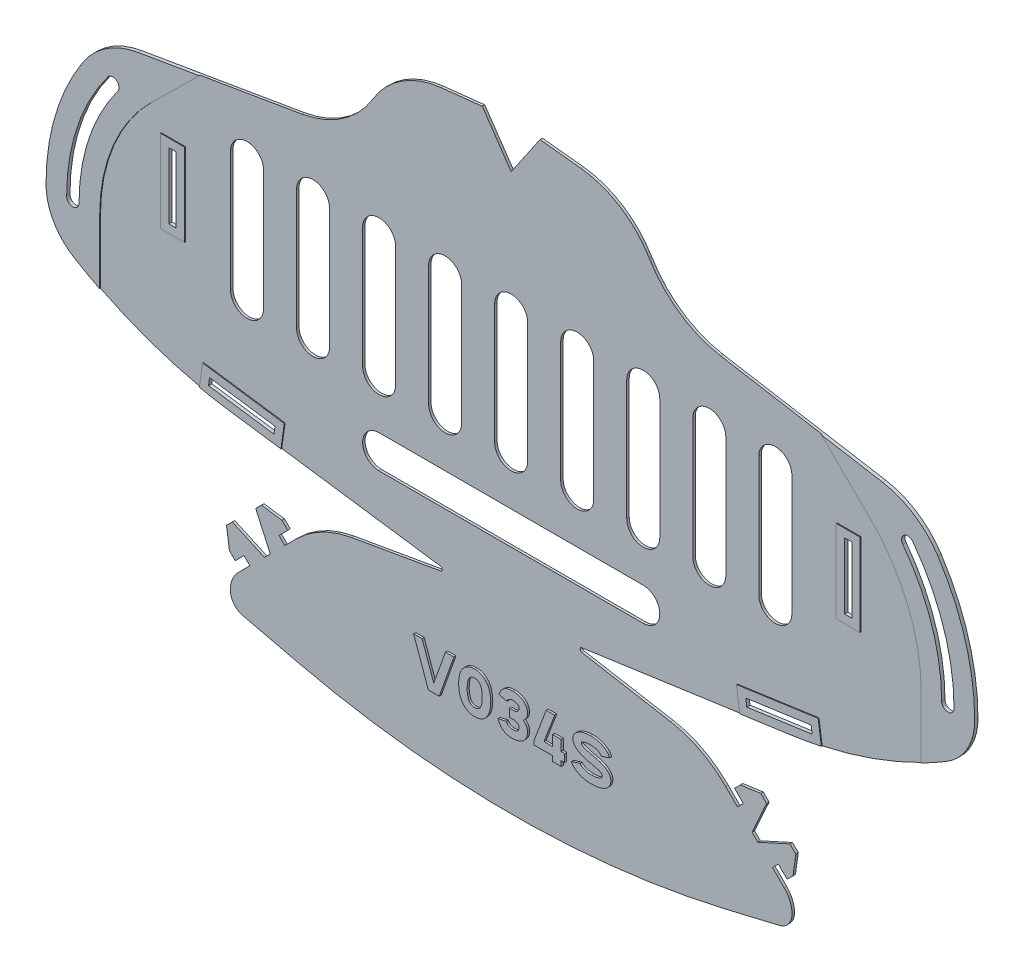
SolidWorks part; units mm, degrees
ref_plane "Front Plane" through (0, 0, 0) normal (0, 0, 1) x (1, 0, 0)
ref_plane "Top Plane" through (0, 0, 0) normal (0, 1, 0) x (1, 0, 0)
ref_plane "Right Plane" through (0, 0, 0) normal (1, 0, 0) x (0, 0, -1)
sketch "Sketch1" plane through (0, 0, 0) normal (0, 0, 1) x (1, 0, 0)
  line L0 (0, 0) -> (0, -145) construction
  line L1 (-14, -102) -> (14, -102) construction
  line L2 (-112.5, -69) -> (112.5, -69) construction
  line L3 (0, -10.2352) -> (-7, 0)
  line L4 (0, -10.2352) -> (7, 0)
  line L5 (7, 0) -> (16.9419, -1.0768)
  line L6 (-90.1804, -30.1909) -> (-50.7439, -23.5)
  line L7 (90.1804, -30.1909) -> (50.7439, -23.5)
  line L8 (-14, -102) -> (-68.2662, -94.2919)
  line L9 (-7, 0) -> (-16.9419, -1.0768)
  line L10 (14, -102) -> (68.2662, -94.2919)
  line L11 (-103.5977, -39) -> (-103.5977, -69) construction
  line L12 (-14, -102) -> (-38.6266, -106.305)
  line L13 (-52, -113.2546) -> (-54.8283, -116.0832)
  line L14 (52, -113.2546) -> (54.8283, -116.0832)
  line L15 (14, -102) -> (38.6266, -106.305)
  line L16 (-54.8283, -116.0832) -> (-56.2426, -114.669)
  line L17 (-56.2426, -114.669) -> (-54.1214, -112.5476)
  line L18 (-54.1214, -112.5476) -> (-55.5356, -111.1334)
  line L19 (-55.5356, -111.1334) -> (-60.4854, -110.4265)
  line L20 (-60.4854, -110.4265) -> (-68.9703, -118.9122)
  line L21 (-64.7275, -123.1546) -> (-63.3132, -124.5688)
  line L22 (-63.3132, -124.5688) -> (-66.1415, -127.3973)
  line L23 (-64.7275, -123.1546) -> (-66.8487, -125.2761)
  line L24 (-66.8487, -125.2761) -> (-68.263, -123.8619)
  line L25 (-68.9703, -118.9122) -> (-68.263, -123.8619)
  line L26 (68.9703, -118.9122) -> (68.263, -123.8619)
  line L27 (66.8487, -125.2761) -> (68.263, -123.8619)
  line L28 (64.7275, -123.1546) -> (66.8487, -125.2761)
  line L29 (63.3132, -124.5688) -> (66.1415, -127.3973)
  line L30 (64.7275, -123.1546) -> (63.3132, -124.5688)
  line L31 (60.4854, -110.4265) -> (68.9703, -118.9122)
  line L32 (55.5356, -111.1334) -> (60.4854, -110.4265)
  line L33 (54.1214, -112.5476) -> (55.5356, -111.1334)
  line L34 (56.2426, -114.669) -> (54.1214, -112.5476)
  line L35 (54.8283, -116.0832) -> (56.2426, -114.669)
  line L36 (-64.9691, -135.8852) -> (-52.4361, -138.8607)
  line L37 (64.9691, -135.8852) -> (52.4361, -138.8607)
  line L38 (-68.9703, -118.9122) -> (-64.7275, -123.1546) construction
  line L39 (-60.4854, -110.4265) -> (-56.2426, -114.669) construction
  arc A0 (-16.9419, -1.0768) -> (-33.4614, -11.6696) centre (-14.5729, -22.9489) ccw
  arc A1 (-33.4614, -11.6696) -> (-50.7439, -23.5) centre (-54.9257, 1.1478) cw
  arc A2 (-103.5977, -39) -> (-90.1804, -30.1909) centre (-86.8349, -49.9091) cw
  arc A3 (-112.5, -69) -> (-103.5977, -39) centre (-57.5, -69) cw
  arc A4 (112.5, -69) -> (103.5977, -39) centre (57.5, -69) ccw
  arc A5 (103.5977, -39) -> (90.1804, -30.1909) centre (86.8349, -49.9091) ccw
  arc A6 (16.9419, -1.0768) -> (33.4614, -11.6696) centre (14.5729, -22.9489) cw
  arc A7 (33.4614, -11.6696) -> (50.7439, -23.5) centre (54.9257, 1.1478) ccw
  arc A8 (-112.5, -69) -> (-105.7111, -81) centre (-98.5, -69) ccw
  arc A9 (-105.7111, -81) -> (-68.2662, -94.2919) centre (-54.2032, 4.7143) ccw
  arc A10 (112.5, -69) -> (105.7111, -81) centre (98.5, -69) cw
  arc A11 (105.7111, -81) -> (68.2662, -94.2919) centre (54.2032, 4.7143) cw
  arc A12 (-38.6266, -106.305) -> (-52, -113.2546) centre (-34.3216, -130.9315) ccw
  arc A13 (38.6266, -106.305) -> (52, -113.2546) centre (34.3216, -130.9315) cw
  arc A14 (-66.1415, -127.3973) -> (-68.0451, -131.9933) centre (-61.5451, -131.9933) ccw
  arc A15 (-68.0451, -131.9933) -> (-64.9691, -135.8852) centre (-64.0451, -131.9933) ccw
  arc A16 (68.0451, -131.9933) -> (64.9691, -135.8852) centre (64.0451, -131.9933) cw
  arc A17 (66.1415, -127.3973) -> (68.0451, -131.9933) centre (61.5451, -131.9933) cw
  arc A19 (-52.4361, -138.8607) -> (0, -145) centre (0, 82) ccw
  arc A20 (52.4361, -138.8607) -> (0, -145) centre (0, 82) cw
  point P8 (0, -102)
  point P11 (0, -69)
  dimension "D5" = 55
  dimension "D11" = 20
  dimension "D13" = 25
  dimension "D16" = 14
  dimension "D15" = 22
  dimension "D18" = 100
  dimension "D22" = 25
  dimension "D31" = 6.5
  dimension "D32" = 4
  dimension "D34" = 227
  dimension "D1" = 145
  dimension "D2" = 28
  dimension "D3" = 43
  dimension "D4" = 76
  dimension "D6" = 225
  dimension "D7" = 14
  dimension "D8" = 12.4
  dimension "D9" = 10
  dimension "D10" = 30
  dimension "D12" = 40
  dimension "D14" = 45.5
  dimension "D17" = 12
  dimension "D19" = 18
  dimension "D20" = 25
  dimension "D21" = 4
  dimension "D23" = 38
  dimension "D24" = 2
  dimension "D25" = 3
  dimension "D26" = 2
  dimension "D27" = 18
  dimension "D29" = 8
  dimension "D30" = 4
extrude "Main Shape" add sketch "Sketch1" along normal blind 0.6
sketch "Sketch2" plane through (0, 0, 0.6) normal (0, 0, 1) x (1, 0, 0)
  line L0 (0, -55) -> (0, 55) construction
  arc A0 (-96.3, -39.9) -> (-106, -69) centre (-57.5, -69) ccw construction
  arc A1 (-97.5, -39) -> (-107.5, -69) centre (-57.5, -69) ccw
  arc A2 (-95.1, -40.8) -> (-104.5, -69) centre (-57.5, -69) ccw
  arc A3 (-95.1, -40.8) -> (-97.5, -39) centre (-96.3, -39.9) ccw
  arc A4 (-107.5, -69) -> (-104.5, -69) centre (-106, -69) ccw
  arc A6 (-103.5977, -39) -> (-112.5, -69) centre (-57.5, -69) ccw construction
  arc A7 (96.3, -39.9) -> (106, -69) centre (57.5, -69) cw construction
  arc A8 (97.5, -39) -> (107.5, -69) centre (57.5, -69) cw
  arc A9 (95.1, -40.8) -> (104.5, -69) centre (57.5, -69) cw
  arc A10 (95.1, -40.8) -> (97.5, -39) centre (96.3, -39.9) cw
  arc A11 (107.5, -69) -> (104.5, -69) centre (106, -69) cw
  point P3 (-103.5111, -53.663)
  point P19 (103.5111, -53.663)
  dimension "D1" = 5
  dimension "D2" = 1.5
extrude "Elastic Attachment Points" cut sketch "Sketch2" against normal through all
sketch "Sketch7" plane through (0, 0, 0.6) normal (0, 0, 1) x (1, 0, 0)
  line L0 (-99.5, -69) -> (-99.5, -84.4384)
  line L1 (-86.8939, -39) -> (-75.3319, -27.6717)
  line L2 (-50.7439, -23.5) -> (-90.1804, -30.1909) construction
  line L3 (-75.3319, -27.6717) -> (-90.1804, -30.1909)
  line L4 (0, -55) -> (0, 55) construction
  line L5 (75.3319, -27.6717) -> (90.1804, -30.1909)
  line L6 (86.8939, -39) -> (75.3319, -27.6717)
  line L7 (99.5, -69) -> (99.5, -84.4384)
  arc A0 (-99.5, -69) -> (-86.8939, -39) centre (-57.5, -69) cw
  arc A1 (-95.1, -40.8) -> (-104.5, -69) centre (-57.5, -69) ccw construction
  arc A2 (-105.7111, -81) -> (-68.2662, -94.2919) centre (-54.2032, 4.7143) ccw construction
  arc A3 (-112.5, -69) -> (-105.7111, -81) centre (-98.5, -69) ccw construction
  arc A4 (-103.5977, -39) -> (-112.5, -69) centre (-57.5, -69) ccw construction
  arc A5 (-90.1804, -30.1909) -> (-103.5977, -39) centre (-86.8349, -49.9091) ccw construction
  arc A6 (-105.7111, -81) -> (-99.5, -84.4384) centre (-54.2032, 4.7143) ccw
  arc A7 (-112.5, -69) -> (-105.7111, -81) centre (-98.5, -69) ccw
  arc A8 (-103.5977, -39) -> (-112.5, -69) centre (-57.5, -69) ccw
  arc A9 (-90.1804, -30.1909) -> (-103.5977, -39) centre (-86.8349, -49.9091) ccw
  arc A10 (90.1804, -30.1909) -> (103.5977, -39) centre (86.8349, -49.9091) cw
  arc A11 (103.5977, -39) -> (112.5, -69) centre (57.5, -69) cw
  arc A12 (112.5, -69) -> (105.7111, -81) centre (98.5, -69) cw
  arc A13 (105.7111, -81) -> (99.5, -84.4384) centre (54.2032, 4.7143) cw
  arc A14 (99.5, -69) -> (86.8939, -39) centre (57.5, -69) ccw
  arc A15 (-107.5, -69) -> (-104.5, -69) centre (-106, -69) ccw construction
  arc A16 (-95.1, -40.8) -> (-97.5, -39) centre (-96.3, -39.9) ccw construction
  arc A17 (-97.5, -39) -> (-107.5, -69) centre (-57.5, -69) ccw construction
  arc A18 (-107.5, -69) -> (-104.5, -69) centre (-106, -69) ccw
  arc A19 (-95.1, -40.8) -> (-97.5, -39) centre (-96.3, -39.9) ccw
  arc A20 (-95.1, -40.8) -> (-104.5, -69) centre (-57.5, -69) ccw
  arc A21 (-97.5, -39) -> (-107.5, -69) centre (-57.5, -69) ccw
  arc A22 (104.5, -69) -> (107.5, -69) centre (106, -69) ccw construction
  arc A23 (97.5, -39) -> (95.1, -40.8) centre (96.3, -39.9) ccw construction
  arc A24 (104.5, -69) -> (95.1, -40.8) centre (57.5, -69) ccw construction
  arc A25 (107.5, -69) -> (97.5, -39) centre (57.5, -69) ccw construction
  arc A26 (104.5, -69) -> (107.5, -69) centre (106, -69) ccw
  arc A27 (97.5, -39) -> (95.1, -40.8) centre (96.3, -39.9) ccw
  arc A28 (104.5, -69) -> (95.1, -40.8) centre (57.5, -69) ccw
  arc A29 (107.5, -69) -> (97.5, -39) centre (57.5, -69) ccw
  dimension "D1" = 5
extrude "Reinforced Attachment Points" add sketch "Sketch7" along normal blind 0.2
sketch "Sketch6" plane through (0, 0, 0.6) normal (0, 0, 1) x (1, 0, 0)
  line L0 (-73.1225, -91.5821) -> (-57.2815, -93.8322)
  line L1 (-57.2815, -93.8322) -> (-57.0283, -92.05)
  line L2 (-57.0283, -92.05) -> (-72.8693, -89.8)
  line L3 (-72.8693, -89.8) -> (-73.1225, -91.5821)
  line L4 (-68.2662, -94.2919) -> (-14, -102) construction
  line L5 (-64.9488, -90.925) -> (-65.202, -92.7071) construction
  line L13 (0, -0.44) -> (0, 0.44) construction
  line L14 (64.9488, -90.925) -> (65.202, -92.7071) construction
  line L15 (73.1225, -91.5821) -> (72.8693, -89.8)
  line L16 (57.0283, -92.05) -> (57.2815, -93.8322)
  line L22 (57.0283, -92.05) -> (72.8693, -89.8)
  line L24 (73.1225, -91.5821) -> (57.2815, -93.8322)
  dimension "D1" = 2
  dimension "D2" = 16
  dimension "D3" = 52
  dimension "D4" = 1.8
extrude "Tab Slits" cut sketch "Sketch6" against normal through all
sketch "Sketch9" plane through (0, 0, 0.6) normal (0, 0, 1) x (1, 0, 0)
  line L4 (-57.2815, -93.8322) -> (-57.0283, -92.05) construction
  line L5 (-73.1225, -91.5821) -> (-57.2815, -93.8322) construction
  line L6 (-72.8693, -89.8) -> (-73.1225, -91.5821) construction
  line L7 (-57.0283, -92.05) -> (-72.8693, -89.8) construction
  line L12 (-57.2815, -93.8322) -> (-57.0283, -92.05)
  line L13 (-73.1225, -91.5821) -> (-57.2815, -93.8322)
  line L14 (-72.8693, -89.8) -> (-73.1225, -91.5821)
  line L15 (-57.0283, -92.05) -> (-72.8693, -89.8)
  line L16 (-55.5826, -96.0935) -> (-54.767, -90.3512)
  line L17 (-68.2662, -94.2919) -> (-14, -102) construction
  line L18 (-54.767, -90.3512) -> (-74.5682, -87.5386)
  line L19 (-74.5682, -87.5386) -> (-75.3475, -93.0248)
  line L20 (-68.2662, -94.2919) -> (-55.5826, -96.0935)
  line L21 (0, -0.44) -> (0, 0.44) construction
  line L22 (68.2662, -94.2919) -> (55.5826, -96.0935)
  line L23 (74.5682, -87.5386) -> (75.3475, -93.0248)
  line L24 (54.767, -90.3512) -> (74.5682, -87.5386)
  line L25 (55.5826, -96.0935) -> (54.767, -90.3512)
  line L26 (57.0283, -92.05) -> (72.8693, -89.8)
  line L27 (72.8693, -89.8) -> (73.1225, -91.5821)
  line L28 (73.1225, -91.5821) -> (57.2815, -93.8322)
  line L29 (57.2815, -93.8322) -> (57.0283, -92.05)
  arc A0 (-99.5, -84.4384) -> (-68.2662, -94.2919) centre (-54.2032, 4.7143) ccw construction
  arc A1 (-75.3475, -93.0248) -> (-68.2662, -94.2919) centre (-54.2032, 4.7143) ccw
  arc A2 (75.3475, -93.0248) -> (68.2662, -94.2919) centre (54.2032, 4.7143) cw
  dimension "D1" = 2
  dimension "D2" = 2
  dimension "D3" = 2
extrude "Reinforced Tab Slits" add sketch "Sketch9" along normal blind 0.2
sketch "Sketch11" plane through (0, 0, 0.6) normal (0, 0, 1) x (1, 0, 0)
  line L0 (-67.5562, -117.4979) -> (-59.7778, -121.0331)
  line L1 (-60.4854, -110.4265) -> (-68.9703, -118.9122) construction
  line L2 (-59.7778, -121.0331) -> (-58.3637, -119.6188)
  line L3 (-58.3637, -119.6188) -> (-61.8996, -111.8408)
  line L4 (-61.8996, -111.8408) -> (-67.5562, -117.4979)
  line L6 (-58.3637, -119.6188) -> (-54.8283, -116.0832) construction
  line L7 (-59.7778, -121.0331) -> (-63.3132, -124.5688) construction
  line L10 (0, -0.44) -> (0, 0.44) construction
  line L11 (59.7778, -121.0331) -> (63.3132, -124.5688) construction
  line L12 (58.3637, -119.6188) -> (54.8283, -116.0832) construction
  line L13 (61.8996, -111.8408) -> (67.5562, -117.4979)
  line L14 (58.3637, -119.6188) -> (61.8996, -111.8408)
  line L15 (59.7778, -121.0331) -> (58.3637, -119.6188)
  line L16 (67.5562, -117.4979) -> (59.7778, -121.0331)
  dimension "D1" = 2
  dimension "D2" = 2
  dimension "D3" = 5
extrude "Tab Flex Relief" cut sketch "Sketch11" against normal through all both and the other way through all
sketch "Sketch3" plane through (0, 0, 0.6) normal (0, 0, 1) x (1, 0, 0)
  line L3 (0, -10.2352) -> (0, -145) construction
  line L4 (-106, -69) -> (-96.3, -69) construction
  line L5 (-96.3, -69) -> (-96.3, -39.9) construction
  line L427 (0, -39.9) -> (0, -69) construction
  line L428 (4, -39.9) -> (4, -69)
  line L429 (-4, -39.9) -> (-4, -69)
  line L444 (-16, -39.9) -> (-16, -69) construction
  line L447 (-12, -39.9) -> (-12, -69)
  line L450 (-20, -39.9) -> (-20, -69)
  line L451 (-32, -39.9) -> (-32, -69) construction
  line L455 (-28, -39.9) -> (-28, -69)
  line L456 (-36, -39.9) -> (-36, -69)
  line L836 (-32, -85) -> (32, -85) construction
  line L837 (-32, -81) -> (32, -81)
  line L838 (-32, -89) -> (32, -89)
  line L839 (-64, -73) -> (64, -73) construction
  line L933 (-48, -39.9) -> (-48, -69) construction
  line L934 (-44, -39.9) -> (-44, -69)
  line L935 (-52, -39.9) -> (-52, -69)
  line L936 (-64, -39.9) -> (-64, -69) construction
  line L937 (-60, -39.9) -> (-60, -69)
  line L938 (-68, -39.9) -> (-68, -69)
  line L939 (16, -39.9) -> (16, -69) construction
  line L940 (12, -39.9) -> (12, -69)
  line L941 (20, -39.9) -> (20, -69)
  line L942 (32, -39.9) -> (32, -69) construction
  line L943 (28, -39.9) -> (28, -69)
  line L944 (36, -39.9) -> (36, -69)
  line L945 (48, -39.9) -> (48, -69) construction
  line L946 (44, -39.9) -> (44, -69)
  line L947 (52, -39.9) -> (52, -69)
  line L948 (64, -39.9) -> (64, -69) construction
  line L949 (60, -39.9) -> (60, -69)
  line L950 (68, -39.9) -> (68, -69)
  arc A2 (-52.4361, -138.8607) -> (52.4361, -138.8607) centre (0, 82) ccw construction
  arc A21 (4, -39.9) -> (-4, -39.9) centre (0, -39.9) ccw
  arc A22 (-4, -69) -> (4, -69) centre (0, -69) ccw
  arc A23 (-12, -39.9) -> (-20, -39.9) centre (-16, -39.9) ccw
  arc A24 (-20, -69) -> (-12, -69) centre (-16, -69) ccw
  arc A25 (-28, -39.9) -> (-36, -39.9) centre (-32, -39.9) ccw
  arc A26 (-36, -69) -> (-28, -69) centre (-32, -69) ccw
  arc A27 (-44, -39.9) -> (-52, -39.9) centre (-48, -39.9) ccw
  arc A28 (-52, -69) -> (-44, -69) centre (-48, -69) ccw
  arc A29 (-60, -39.9) -> (-68, -39.9) centre (-64, -39.9) ccw
  arc A30 (-68, -69) -> (-60, -69) centre (-64, -69) ccw
  arc A31 (12, -39.9) -> (20, -39.9) centre (16, -39.9) cw
  arc A32 (20, -69) -> (12, -69) centre (16, -69) cw
  arc A33 (28, -39.9) -> (36, -39.9) centre (32, -39.9) cw
  arc A34 (36, -69) -> (28, -69) centre (32, -69) cw
  arc A35 (44, -39.9) -> (52, -39.9) centre (48, -39.9) cw
  arc A36 (52, -69) -> (44, -69) centre (48, -69) cw
  arc A37 (60, -39.9) -> (68, -39.9) centre (64, -39.9) cw
  arc A38 (68, -69) -> (60, -69) centre (64, -69) cw
  arc A39 (-32, -81) -> (-32, -89) centre (-32, -85) ccw
  arc A40 (32, -89) -> (32, -81) centre (32, -85) ccw
  point P3 (-16, -54.45)
  point P18 (-32, -54.45)
  point P30 (-48, -54.45)
  point P37 (-64, -54.45)
  point P43 (16, -54.45)
  point P50 (32, -54.45)
  point P57 (48, -54.45)
  point P64 (64, -54.45)
  point P71 (0, -85)
  point P414 (0, -54.45)
  dimension "D5" = 8
  dimension "D1" = 8
  dimension "D2" = 5
  dimension "D3" = 8
  dimension "D4" = 8
extrude "Breathing Slits" cut sketch "Sketch3" against normal through all
sketch "Sketch8" plane through (0, 0, 0.6) normal (0, 0, 1) x (1, 0, 0)
  line L0 (-67.0266, -128.5) -> (67.0266, -128.5) construction
  line L1 (0, -10.2352) -> (0, -145) construction
  arc A0 (-52.4361, -138.8607) -> (52.4361, -138.8607) centre (0, 82) ccw construction
  arc A1 (-66.1415, -127.3973) -> (-68.0451, -131.9933) centre (-61.5451, -131.9933) ccw construction
  text T0 "<b>V034S</b>" font "Double Porter 3" height 10
  point P9 (0, -128.5)
  dimension "D2" = 16.5
extrude "Version Number" add sketch "Sketch8" along normal blind 0.5
fillet "Fillet1" radius 0.5 2 edges at (-14, -102, 0.3) (14, -102, 0.3)
sketch "Sketch12" plane through (0, 0, 0.6) normal (0, 0, 1) x (1, 0, 0)
  line L0 (-106, -69) -> (-96.3, -69) construction
  line L1 (-96.3, -69) -> (-96.3, -39.9) construction
  line L2 (-82.7459, -46.45) -> (-80.9459, -46.45)
  line L3 (-82.7459, -46.45) -> (-82.7459, -62.45)
  line L4 (-82.7459, -62.45) -> (-80.9459, -62.45)
  line L5 (-80.9459, -46.45) -> (-80.9459, -62.45)
  line L6 (0, -10.2352) -> (0, -145) construction
  line L9 (80.9459, -46.45) -> (80.9459, -62.45)
  line L10 (82.7459, -62.45) -> (80.9459, -62.45)
  line L11 (82.7459, -46.45) -> (82.7459, -62.45)
  line L12 (82.7459, -46.45) -> (80.9459, -46.45)
  arc A1 (-52.4361, -138.8607) -> (52.4361, -138.8607) centre (0, 82) ccw construction
  point P9 (0, 0)
  point P13 (-96.3, -54.45)
  point P18 (-82.7459, -54.45)
  dimension "D1" = 16
  dimension "D2" = 1.8
  dimension "D3" = 80.9459
extrude "Tab Overlay Slit" cut sketch "Sketch12" against normal through all both and the other way through all
sketch "Sketch13" plane through (0, 0, 0.6) normal (0, 0, 1) x (1, 0, 0)
  line L0 (-80.9459, -62.45) -> (-82.7459, -62.45) construction
  line L1 (-84.7459, -44.45) -> (-78.9459, -44.45)
  line L2 (-84.7459, -44.45) -> (-84.7459, -64.45)
  line L3 (-84.7459, -64.45) -> (-78.9459, -64.45)
  line L4 (-78.9459, -44.45) -> (-78.9459, -64.45)
  line L5 (-82.7459, -62.45) -> (-82.7459, -46.45) construction
  line L6 (-80.9459, -46.45) -> (-80.9459, -62.45) construction
  line L7 (-82.7459, -46.45) -> (-80.9459, -46.45) construction
  line L8 (-80.9459, -62.45) -> (-82.7459, -62.45)
  line L9 (-80.9459, -46.45) -> (-80.9459, -62.45)
  line L10 (-82.7459, -46.45) -> (-80.9459, -46.45)
  line L11 (-82.7459, -62.45) -> (-82.7459, -46.45)
  line L12 (0, -0.44) -> (0, 0.44) construction
  line L13 (82.7459, -62.45) -> (82.7459, -46.45)
  line L14 (82.7459, -46.45) -> (80.9459, -46.45)
  line L15 (80.9459, -46.45) -> (80.9459, -62.45)
  line L16 (80.9459, -62.45) -> (82.7459, -62.45)
  line L17 (78.9459, -44.45) -> (78.9459, -64.45)
  line L18 (84.7459, -64.45) -> (78.9459, -64.45)
  line L19 (84.7459, -44.45) -> (84.7459, -64.45)
  line L20 (84.7459, -44.45) -> (78.9459, -44.45)
  point P8 (-81.8459, -64.45)
  point P9 (-81.8459, -62.45)
  point P10 (-82.7459, -54.45)
  point P11 (-84.7459, -54.45)
  dimension "D1" = 2
  dimension "D2" = 2
extrude "Tab Overlay Reinforcement" add sketch "Sketch13" along normal blind 0.2
